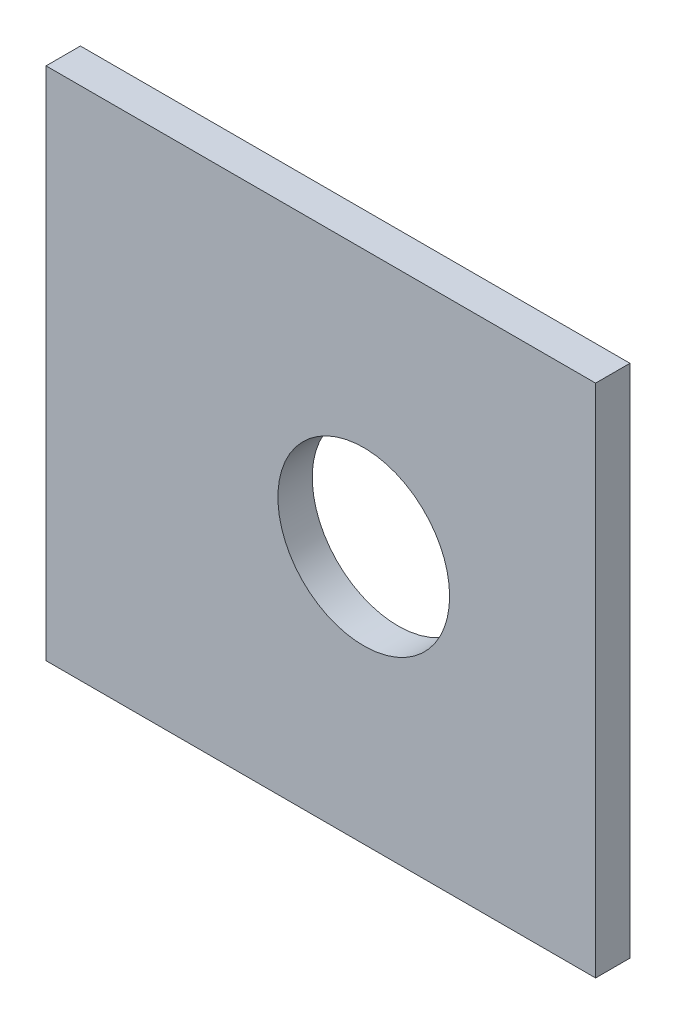
SolidWorks part; units mm, degrees
ref_plane "Front Plane" through (0, 0, 0) normal (0, 0, 1) x (1, 0, 0)
ref_plane "Top Plane" through (0, 0, 0) normal (0, 1, 0) x (1, 0, 0)
ref_plane "Right Plane" through (0, 0, 0) normal (1, 0, 0) x (0, 0, -1)
sketch "Sketch1" plane through (0, 0, 0) normal (0, 0, 1) x (1, 0, 0)
  line L1 (-37, -30) -> (27, -30)
  line L2 (-37, -30) -> (-37, 30)
  line L3 (-37, 30) -> (27, 30)
  line L4 (27, -30) -> (27, 30)
  circle A0 centre (0, 0) radius 10
  point P0 (0, 0)
  point P8 (0, 0)
  point P9 (-37, 0)
  point P10 (0, 0)
  point P11 (0, 0)
  dimension "D3" = 20
  dimension "D1" = 37
  dimension "D2" = 60
  dimension "D5" = 27
extrude "Boss-Extrude1" add sketch "Sketch1" along normal blind 4
